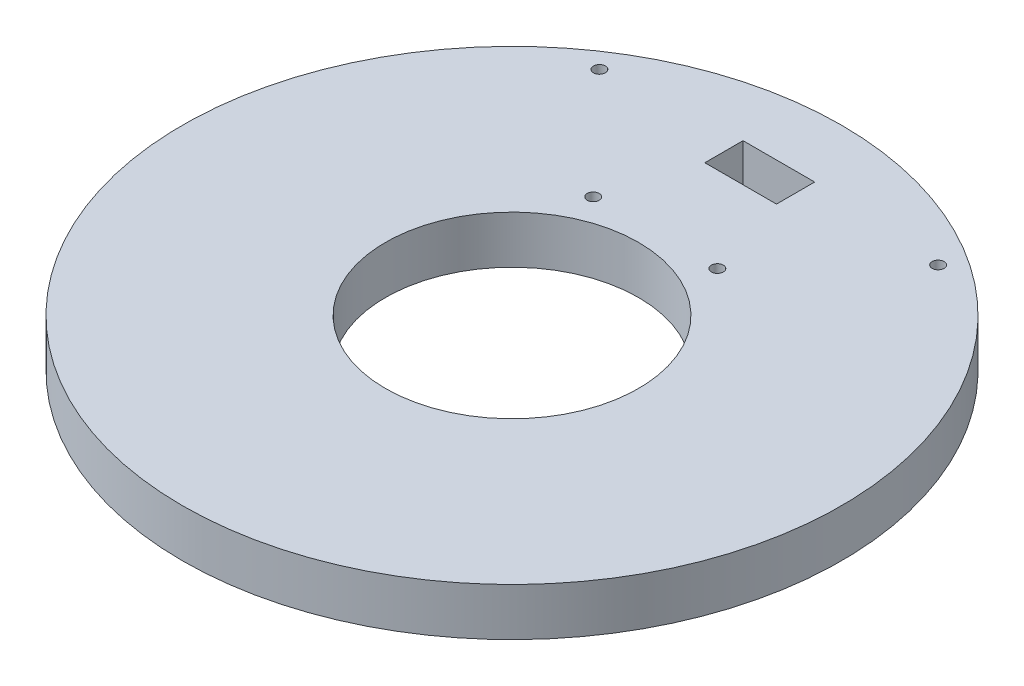
SolidWorks part; units mm, degrees
ref_plane "Front Plane" through (0, 0, 0) normal (0, 0, 1) x (1, 0, 0)
ref_plane "Top Plane" through (0, 0, 0) normal (0, 1, 0) x (1, 0, 0)
ref_plane "Right Plane" through (0, 0, 0) normal (1, 0, 0) x (0, 0, -1)
sketch "Sketch1" plane through (0, 0, 0) normal (0, 1, 0) x (1, 0, 0)
  circle A0 centre (0, 0) radius 26.5
  circle A1 centre (0, 0) radius 69
  point P5 (0, 0)
  dimension "D1" = 53
  dimension "D2" = 138
extrude "Boss-Extrude1" add sketch "Sketch1" along normal blind 10
sketch "Sketch2" plane through (0, 0, 0) normal (0, -1, 0) x (1, 0, 0)
  line L0 (0, 0) -> (-13, -30) construction
  line L1 (-8.7574, -30) -> (-13, -34.2426)
  line L2 (-8.7574, -30) -> (-13, -25.7574)
  line L3 (-13, -25.7574) -> (-17.2426, -30)
  line L4 (-13, -34.2426) -> (-17.2426, -30)
  line L5 (-8.7574, -30) -> (-17.2426, -30) construction
  line L6 (-13, -25.7574) -> (-13, -34.2426) construction
  line L7 (17.2426, -30) -> (13, -34.2426)
  line L8 (17.2426, -30) -> (13, -25.7574)
  line L9 (13, -25.7574) -> (8.7574, -30)
  line L10 (13, -34.2426) -> (8.7574, -30)
  line L11 (17.2426, -30) -> (8.7574, -30) construction
  line L12 (13, -25.7574) -> (13, -34.2426) construction
  line L13 (0, 0) -> (13, -30) construction
  line L14 (-35.46, -53.7582) -> (-13, -30) construction
  line L15 (-31.2174, -53.7582) -> (-35.46, -58.0009)
  line L16 (-31.2174, -53.7582) -> (-35.46, -49.5156)
  line L17 (-35.46, -49.5156) -> (-39.7026, -53.7582)
  line L18 (-35.46, -58.0009) -> (-39.7026, -53.7582)
  line L19 (-31.2174, -53.7582) -> (-39.7026, -53.7582) construction
  line L20 (-35.46, -49.5156) -> (-35.46, -58.0009) construction
  line L21 (39.7026, -53.7582) -> (35.46, -58.0009)
  line L22 (39.7026, -53.7582) -> (35.46, -49.5156)
  line L23 (35.46, -49.5156) -> (31.2174, -53.7582)
  line L24 (35.46, -58.0009) -> (31.2174, -53.7582)
  line L25 (39.7026, -53.7582) -> (31.2174, -53.7582) construction
  line L26 (35.46, -49.5156) -> (35.46, -58.0009) construction
  line L27 (13, -30) -> (35.46, -53.7582) construction
  point P0 (13, -30)
  point P4 (-13, -30)
  point P11 (35.46, -53.7582)
  point P13 (-35.46, -53.7582)
  point P24 (30.9802, -56.4587)
  dimension "D1" = 26
  dimension "D2" = 30
  dimension "D3" = 6
  dimension "D4" = 64.4
  dimension "D5" = 64.4
  dimension "D6" = 70.92
  dimension "D7" = 6
extrude "Cut-Extrude1" cut sketch "Sketch2" against normal blind 4.5 contours L4 L1 L2 L3 | L18 L15 L16 L17 | L10 L7 L8 L9 | L24 L21 L22 L23
sketch "Sketch3" plane through (0, 0, 0) normal (0, -1, 0) x (1, 0, 0)
  line L1 (7.5, -55.875) -> (-7.5, -55.875)
  line L2 (7.5, -55.875) -> (7.5, -47.875)
  line L3 (7.5, -47.875) -> (-7.5, -47.875)
  line L4 (-7.5, -55.875) -> (-7.5, -47.875)
  line L5 (7.5, -55.875) -> (-7.5, -47.875) construction
  line L6 (7.5, -47.875) -> (-7.5, -55.875) construction
  point P0 (0, -51.875)
  point P5 (0, 0)
  dimension "D1" = 51.875
  dimension "D2" = 8
  dimension "D3" = 15
extrude "Cut-Extrude2" cut sketch "Sketch3" against normal through all
sketch "Sketch4" plane through (0, 0, 0) normal (0, -1, 0) x (1, 0, 0)
  line L0 (31.2174, -53.7582) -> (35.46, -58.0009) construction
  line L1 (35.46, -58.0009) -> (39.7026, -53.7582) construction
  line L2 (39.7026, -53.7582) -> (35.46, -49.5156) construction
  line L3 (35.46, -49.5156) -> (31.2174, -53.7582) construction
  line L4 (8.7574, -30) -> (13, -34.2426) construction
  line L5 (13, -34.2426) -> (17.2426, -30) construction
  line L6 (17.2426, -30) -> (13, -25.7574) construction
  line L7 (13, -25.7574) -> (8.7574, -30) construction
  line L8 (-39.7026, -53.7582) -> (-35.46, -58.0009) construction
  line L9 (-35.46, -58.0009) -> (-31.2174, -53.7582) construction
  line L10 (-31.2174, -53.7582) -> (-35.46, -49.5156) construction
  line L11 (-35.46, -49.5156) -> (-39.7026, -53.7582) construction
  line L12 (-17.2426, -30) -> (-13, -34.2426) construction
  line L13 (-13, -34.2426) -> (-8.7574, -30) construction
  line L14 (-8.7574, -30) -> (-13, -25.7574) construction
  line L15 (-13, -25.7574) -> (-17.2426, -30) construction
  line L16 (31.2174, -53.7582) -> (35.46, -58.0009) construction
  line L17 (35.46, -58.0009) -> (39.7026, -53.7582) construction
  line L18 (39.7026, -53.7582) -> (35.46, -49.5156) construction
  line L19 (35.46, -49.5156) -> (31.2174, -53.7582) construction
  line L20 (8.7574, -30) -> (13, -34.2426) construction
  line L21 (13, -34.2426) -> (17.2426, -30) construction
  line L22 (17.2426, -30) -> (13, -25.7574) construction
  line L23 (13, -25.7574) -> (8.7574, -30) construction
  line L24 (-39.7026, -53.7582) -> (-35.46, -58.0009) construction
  line L25 (-35.46, -58.0009) -> (-31.2174, -53.7582) construction
  line L26 (-31.2174, -53.7582) -> (-35.46, -49.5156) construction
  line L27 (-35.46, -49.5156) -> (-39.7026, -53.7582) construction
  line L28 (-17.2426, -30) -> (-13, -34.2426) construction
  line L29 (-13, -34.2426) -> (-8.7574, -30) construction
  line L30 (-8.7574, -30) -> (-13, -25.7574) construction
  line L31 (-13, -25.7574) -> (-17.2426, -30) construction
  circle A0 centre (-13, -30) radius 1.25
  circle A1 centre (13, -30) radius 1.25
  circle A2 centre (-35.46, -53.7582) radius 1.25
  circle A3 centre (35.46, -53.7582) radius 1.25
  point P24 (0, 0)
  point P26 (0, 0)
  point P27 (0, 0)
  point P29 (0, 0)
  point P30 (0, 0)
  point P31 (0, 0)
  point P33 (0, 0)
  point P34 (0, 0)
  dimension "D1" = 2.5
extrude "Cut-Extrude3" cut sketch "Sketch4" against normal through all
sketch "Sketch5" plane through (0, 0, 0) normal (0, -1, 0) x (1, 0, 0)
  line L0 (-43, -46.7253) -> (-7.5, -47.875) construction
  line L1 (7.5, -47.875) -> (43, -46.7253) construction
  line L2 (-44.9013, 44.9013) -> (-7.5, -47.875) construction
  line L3 (7.5, -47.875) -> (44.9013, 44.9013) construction
  circle A2 centre (-44.9013, 44.9013) radius 2.75
  circle A3 centre (44.9013, 44.9013) radius 2.75
  circle A4 centre (-43, -46.7253) radius 2.75
  circle A5 centre (43, -46.7253) radius 2.75
  dimension "D1" = 89.8026
  dimension "D4" = 5.5
  dimension "D5" = 63.5
  dimension "D7" = 86
  dimension "D2" = 63.5
  dimension "D3" = 63.5
  dimension "D6" = 63.5
extrude "Cut-Extrude4" cut sketch "Sketch5" against normal blind 8.2
